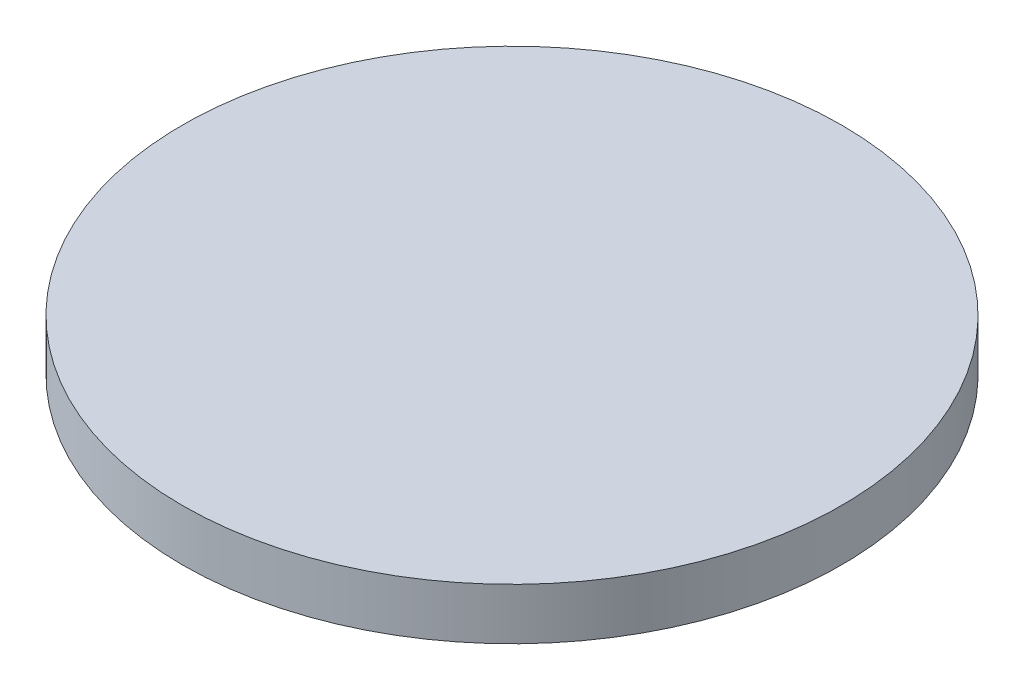
SolidWorks part; units mm, degrees
ref_plane "Front Plane" through (0, 0, 0) normal (0, 0, 1) x (1, 0, 0)
ref_plane "Top Plane" through (0, 0, 0) normal (0, 1, 0) x (1, 0, 0)
ref_plane "Right Plane" through (0, 0, 0) normal (1, 0, 0) x (0, 0, -1)
sketch "Sketch1" plane through (0, 0, 0) normal (0, 1, 0) x (1, 0, 0)
  circle A0 centre (0, 0) radius 320
  dimension "D1" = 640
extrude "Boss-Extrude1" add sketch "Sketch1" along normal blind 50
sketch "Sketch3" plane through (0, 0, 0) normal (0, -1, 0) x (1, 0, 0)
  line L0 (0, 320) -> (0, -320) construction
  line L1 (-320, 0) -> (320, 0) construction
  circle A0 centre (0, 0) radius 320 construction
sketch "Sketch4" plane through (0, 0, 0) normal (0, -1, 0) x (1, 0, 0)
  line L0 (0, 320) -> (0, -320) construction
  circle A0 centre (0, 0) radius 32.5
  dimension "D1" = 65
extrude "Boss-Extrude2" add sketch "Sketch4" along normal blind 15
sketch "Sketch5" plane through (0, 50, 0) normal (0, 1, 0) x (1, 0, 0)
  line L0 (0, 320) -> (0, -320) construction
  line L1 (-320, 0) -> (320, 0) construction
  circle A0 centre (0, 0) radius 320 construction
sketch "Sketch6" plane through (0, 50, 0) normal (0, 1, 0) x (1, 0, 0)
  line L0 (0, 320) -> (0, -320) construction
  circle A0 centre (0, 0) radius 320 construction
  dimension "D1" = 640
